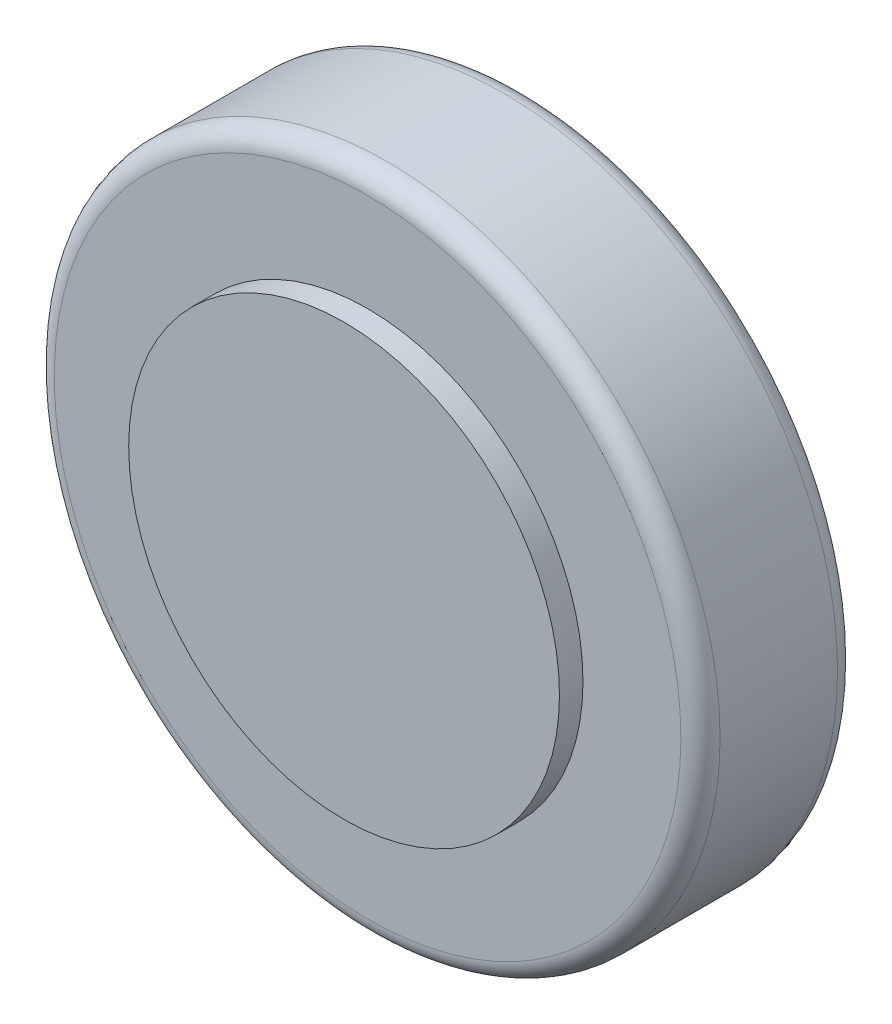
SolidWorks part; units mm, degrees
ref_plane "前视基准面" through (0, 0, 0) normal (0, 0, 1) x (1, 0, 0)
ref_plane "上视基准面" through (0, 0, 0) normal (0, 1, 0) x (1, 0, 0)
ref_plane "右视基准面" through (0, 0, 0) normal (1, 0, 0) x (0, 0, -1)
other "Configuration Table"
sketch "草图1" plane through (0, 0, 0) normal (0, 1, 0) x (1, 0, 0)
  line L0 (0, 565.0473) -> (0, -463.9443) construction
  line L1 (0, 26) -> (0, -26)
  line L2 (5, 26) -> (55, 26)
  line L3 (0, -26) -> (55, -26)
  line L4 (85, 15) -> (85, -15)
  line L9 (55, 20) -> (80, 20)
  line L10 (55, -20) -> (80, -20)
  line L11 (0, 20) -> (850, 20) construction
  line L12 (0, -20) -> (850, -20) construction
  line L13 (55, 20) -> (55, 26)
  line L14 (55, -20) -> (55, -26)
  line L15 (0, 26) -> (850, 26) construction
  line L16 (0, -26) -> (850, -26) construction
  line L18 (0, 26) -> (0, 31)
  line L19 (5, 26) -> (5, 31)
  line L20 (0, 31) -> (5, 31)
  arc A0 (80, -20) -> (85, -15) centre (80, -15) ccw
  arc A1 (80, 20) -> (85, 15) centre (80, 15) cw
  point P3 (0, 0)
  point P19 (85, -20)
  point P22 (85, 20)
  point P23 (0.2635, -26)
  dimension "D7" = 5
  dimension "D1" = 52
  dimension "D2" = 85
  dimension "D5" = 30
  dimension "D6" = 30
  dimension "D8" = 5
  dimension "D9" = 5
  dimension "D3" = 6
  dimension "D4" = 6
revolve "旋转1" add sketch "草图1" angle 360 about L18
